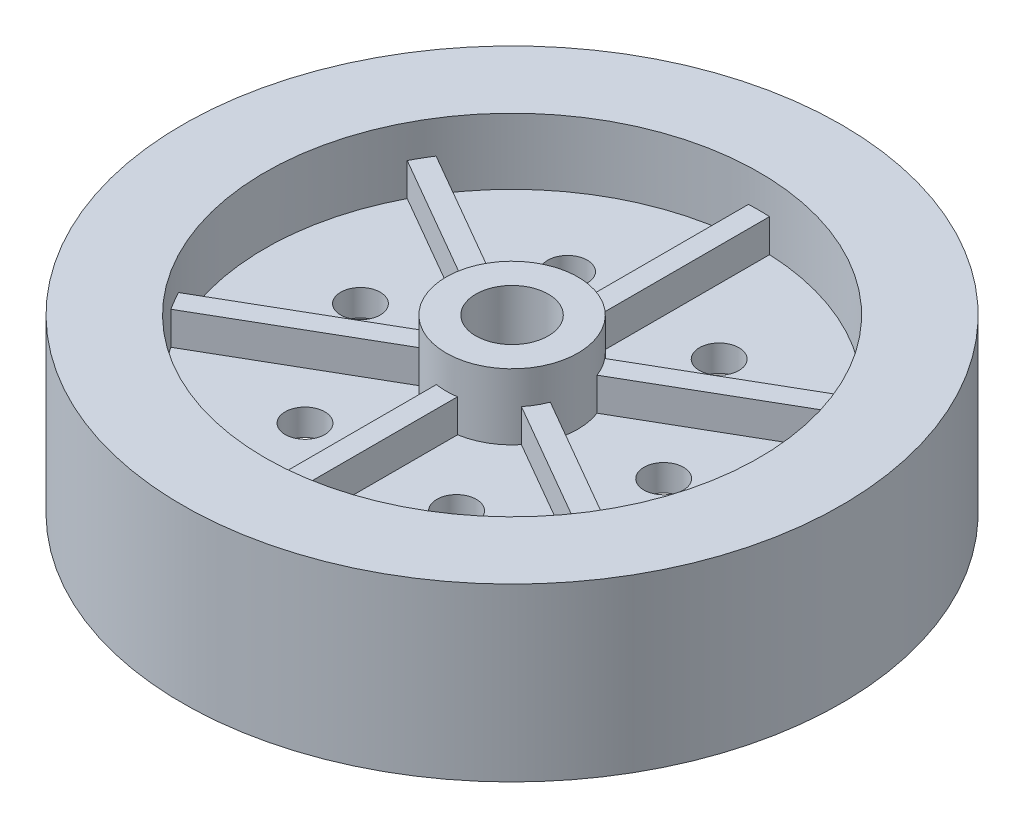
SolidWorks part; units mm, degrees
ref_plane "Front Plane" through (0, 0, 0) normal (0, 0, 1) x (1, 0, 0)
ref_plane "Top Plane" through (0, 0, 0) normal (0, 1, 0) x (1, 0, 0)
ref_plane "Right Plane" through (0, 0, 0) normal (1, 0, 0) x (0, 0, -1)
sketch "Sketch1" plane through (0, 0, 0) normal (0, 1, 0) x (1, 0, 0)
  circle A0 centre (0, 0) radius 37.5
  circle A1 centre (0, 0) radius 50
  dimension "D1" = 100
  dimension "D2" = 75
extrude "Boss-Extrude1" add sketch "Sketch1" along normal blind 26
ref_plane "Plane1" through (0, 12, 0) normal (0, 1, 0) x (1, 0, 0)
sketch "Sketch3" plane through (0, 12, 0) normal (0, 1, 0) x (1, 0, 0)
  line L0 (0, 10) -> (0, 37.5) construction
  line L1 (1.6032, 37.4657) -> (1.6032, 9.8707)
  line L2 (-1.6032, 37.4657) -> (-1.6032, 9.8707)
  line L3 (31.6447, 20.1212) -> (7.7467, 6.3237)
  line L4 (33.2478, 17.3445) -> (9.3498, 3.5469)
  line L5 (33.2478, -17.3445) -> (9.3498, -3.5469)
  line L6 (31.6447, -20.1212) -> (7.7467, -6.3237)
  line L7 (1.6032, -37.4657) -> (1.6032, -9.8707)
  line L8 (-1.6032, -37.4657) -> (-1.6032, -9.8707)
  line L9 (-31.6447, -20.1212) -> (-7.7467, -6.3237)
  line L10 (-33.2478, -17.3445) -> (-9.3498, -3.5469)
  line L11 (-33.2478, 17.3445) -> (-9.3498, 3.5469)
  line L12 (-31.6447, 20.1212) -> (-7.7467, 6.3237)
  arc A0 (-7.7467, 6.3237) -> (-9.3498, 3.5469) centre (0, 0) ccw
  arc A1 (1.6032, 37.4657) -> (-1.6032, 37.4657) centre (0, 0) ccw
  arc A2 (-31.6447, 20.1212) -> (-33.2478, 17.3445) centre (0, 0) ccw
  arc A3 (-33.2478, -17.3445) -> (-31.6447, -20.1212) centre (0, 0) ccw
  arc A4 (1.6032, 9.8707) -> (-1.6032, 9.8707) centre (0, 0) ccw
  arc A5 (9.3498, 3.5469) -> (7.7467, 6.3237) centre (0, 0) ccw
  arc A6 (7.7467, -6.3237) -> (9.3498, -3.5469) centre (0, 0) ccw
  arc A7 (-9.3498, -3.5469) -> (-7.7467, -6.3237) centre (0, 0) ccw
  arc A8 (-1.6032, -9.8707) -> (1.6032, -9.8707) centre (0, 0) ccw
  arc A9 (-1.6032, -37.4657) -> (1.6032, -37.4657) centre (0, 0) ccw
  arc A10 (31.6447, -20.1212) -> (33.2478, -17.3445) centre (0, 0) ccw
  arc A11 (33.2478, 17.3445) -> (31.6447, 20.1212) centre (0, 0) ccw
  point P6 (1.6032, 37.4657)
  point P9 (-1.6032, 9.8707)
  point P10 (-1.6032, 37.4657)
  point P36 (0, 0)
  dimension "D1" = 6
extrude "Boss-Extrude3" add sketch "Sketch3" along normal blind 9
sketch "Sketch9" plane through (0, 26, 0) normal (0, 1, 0) x (1, 0, 0)
  circle A0 centre (0, 0) radius 10
  circle A1 centre (0, 0) radius 5.5
  dimension "D1" = 11
  dimension "D2" = 20
extrude "Boss-Extrude4" add sketch "Sketch9" against normal blind 14
sketch "Sketch10" plane through (0, 12, 0) normal (0, 1, 0) x (1, 0, 0)
  line L0 (0, 0) -> (23, 0) construction
  line L1 (7.7467, 6.3237) -> (31.6447, 20.1212)
  line L2 (33.2478, 17.3445) -> (9.3498, 3.5469)
  line L3 (31.6447, -20.1212) -> (7.7467, -6.3237)
  line L4 (9.3498, -3.5469) -> (33.2478, -17.3445)
  line L5 (-1.6032, -37.4657) -> (-1.6032, -9.8707)
  line L6 (1.6032, -9.8707) -> (1.6032, -37.4657)
  line L7 (-33.2478, -17.3445) -> (-9.3498, -3.5469)
  line L8 (-7.7467, -6.3237) -> (-31.6447, -20.1212)
  line L9 (-31.6447, 20.1212) -> (-7.7467, 6.3237)
  line L10 (-9.3498, 3.5469) -> (-33.2478, 17.3445)
  line L11 (1.6032, 37.4657) -> (1.6032, 9.8707)
  line L12 (-1.6032, 9.8707) -> (-1.6032, 37.4657)
  arc A1 (-9.3498, 3.5469) -> (-9.3498, -3.5469) centre (0, 0) ccw
  circle A2 centre (23, 0) radius 3
  circle A3 centre (11.5, -19.9186) radius 3
  circle A4 centre (-11.5, -19.9186) radius 3
  circle A5 centre (-23, 0) radius 3
  circle A6 centre (-11.5, 19.9186) radius 3
  circle A7 centre (11.5, 19.9186) radius 3
  arc A8 (1.6032, -37.4657) -> (31.6447, -20.1212) centre (0, 0) ccw
  arc A9 (-1.6032, 9.8707) -> (-7.7467, 6.3237) centre (0, 0) ccw
  arc A10 (7.7467, 6.3237) -> (1.6032, 9.8707) centre (0, 0) ccw
  arc A11 (9.3498, -3.5469) -> (9.3498, 3.5469) centre (0, 0) ccw
  arc A12 (-7.7467, -6.3237) -> (-1.6032, -9.8707) centre (0, 0) ccw
  arc A13 (1.6032, -9.8707) -> (7.7467, -6.3237) centre (0, 0) ccw
  arc A14 (-31.6447, -20.1212) -> (-1.6032, -37.4657) centre (0, 0) ccw
  arc A15 (-33.2478, 17.3445) -> (-33.2478, -17.3445) centre (0, 0) ccw
  arc A16 (-1.6032, 37.4657) -> (-31.6447, 20.1212) centre (0, 0) ccw
  arc A17 (33.2478, -17.3445) -> (33.2478, 17.3445) centre (0, 0) ccw
  arc A18 (31.6447, 20.1212) -> (1.6032, 37.4657) centre (0, 0) ccw
  point P47 (0, 0)
  dimension "D3" = 6
  dimension "D2" = 23
  dimension "D1" = 6
extrude "Boss-Extrude5" add sketch "Sketch10" along normal blind 4
